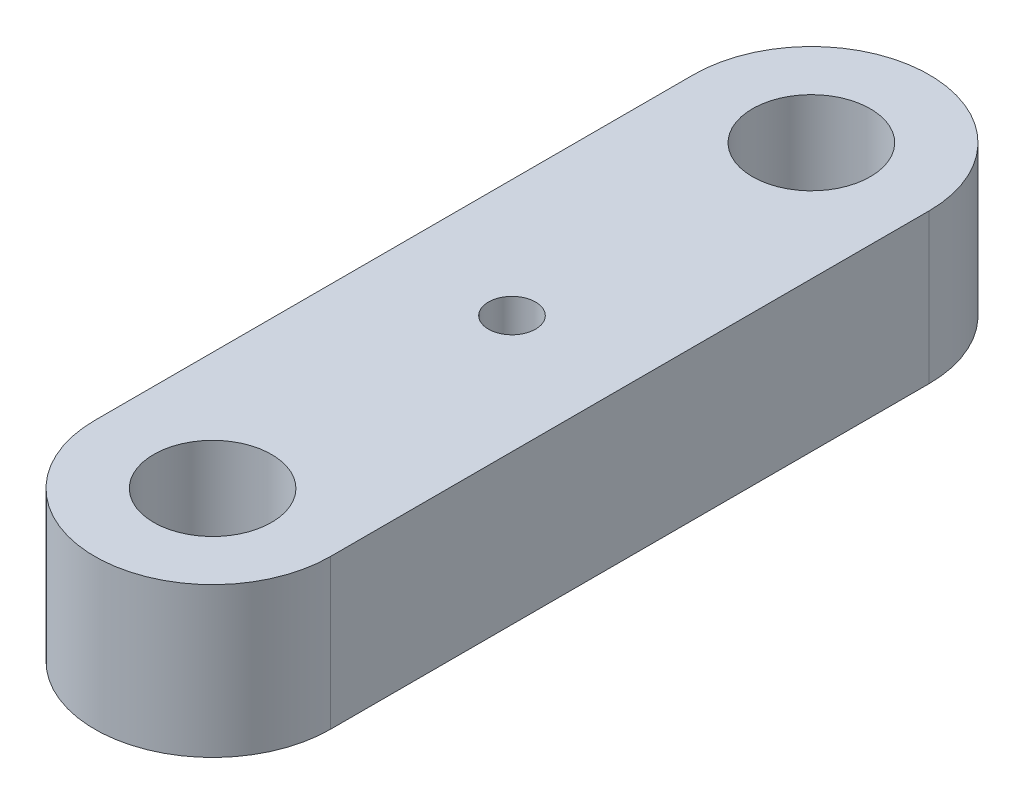
SolidWorks part; units mm, degrees
ref_plane "Front Plane" through (0, 0, 0) normal (0, 0, 1) x (1, 0, 0)
ref_plane "Top Plane" through (0, 0, 0) normal (0, 1, 0) x (1, 0, 0)
ref_plane "Right Plane" through (0, 0, 0) normal (1, 0, 0) x (0, 0, -1)
sketch "Sketch1" plane through (0, 0, 0) normal (0, 1, 0) x (1, 0, 0)
  line L0 (0, -6.35) -> (0, 6.35) construction
  line L1 (-2.5, -6.35) -> (-2.5, 6.35)
  line L2 (2.5, -6.35) -> (2.5, 6.35)
  arc A0 (-2.5, -6.35) -> (2.5, -6.35) centre (0, -6.35) ccw
  arc A1 (2.5, 6.35) -> (-2.5, 6.35) centre (0, 6.35) ccw
  circle A2 centre (0, 6.35) radius 1.25
  circle A3 centre (0, -6.35) radius 1.25
  circle A4 centre (0, 0) radius 0.5
  point P2 (0, 0)
  dimension "D2" = 2.5
  dimension "D4" = 1
  dimension "D1" = 5
  dimension "D3" = 12.7
extrude "Boss-Extrude1" add sketch "Sketch1" along normal blind 3.175
